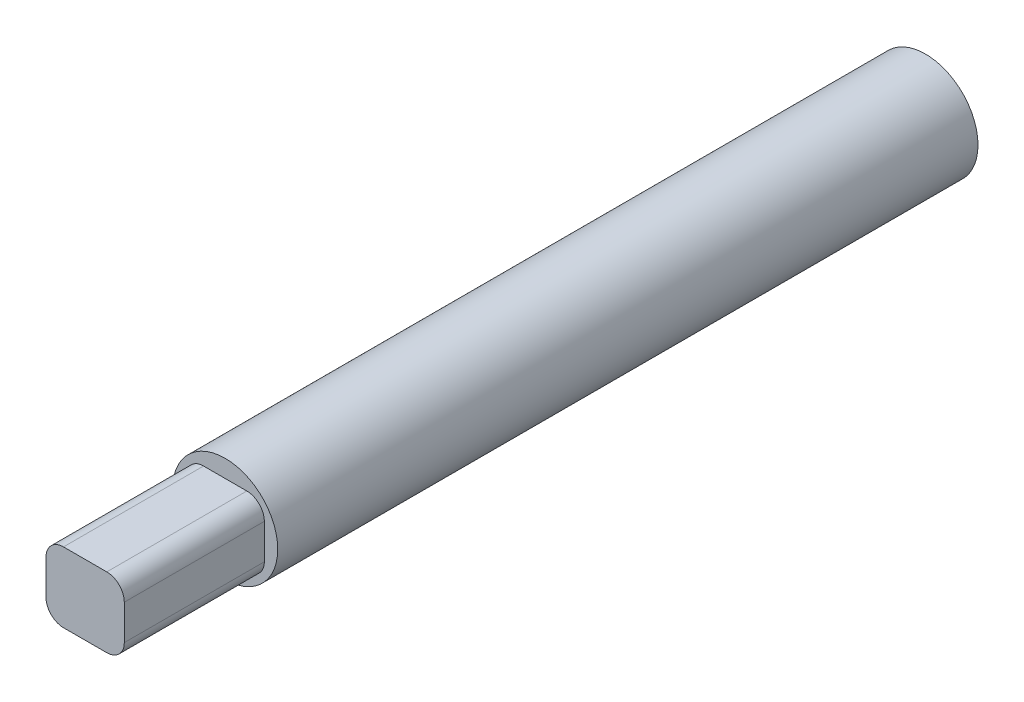
SolidWorks part; units mm, degrees
ref_plane "Front Plane" through (0, 0, 0) normal (0, 0, 1) x (1, 0, 0)
ref_plane "Top Plane" through (0, 0, 0) normal (0, 1, 0) x (1, 0, 0)
ref_plane "Right Plane" through (0, 0, 0) normal (1, 0, 0) x (0, 0, -1)
sketch "Sketch1" plane through (0, 0, 0) normal (0, 0, 1) x (1, 0, 0)
  circle A0 centre (0, 0) radius 3
  dimension "D1" = 6
extrude "Boss-Extrude1" add sketch "Sketch1" along normal blind 40
sketch "Sketch2" plane through (0, 0, 40) normal (0, 0, 1) x (1, 0, 0)
  line L1 (2.2361, -2) -> (-2.2361, -2)
  line L2 (2.2361, -2) -> (2.2361, 2)
  line L3 (2.2361, 2) -> (-2.2361, 2)
  line L4 (-2.2361, -2) -> (-2.2361, 2)
  line L5 (2.2361, -2) -> (-2.2361, 2) construction
  line L6 (2.2361, 2) -> (-2.2361, -2) construction
  circle A2 centre (0, 0) radius 3 construction
  point P0 (0, 0)
  dimension "D1" = 4
extrude "Boss-Extrude2" add sketch "Sketch2" along normal blind 8
fillet "Fillet1" radius 1 4 edges at (2.2361, -2, 44) (-2.2361, -2, 44) (2.2361, 2, 44) (-2.2361, 2, 44)
